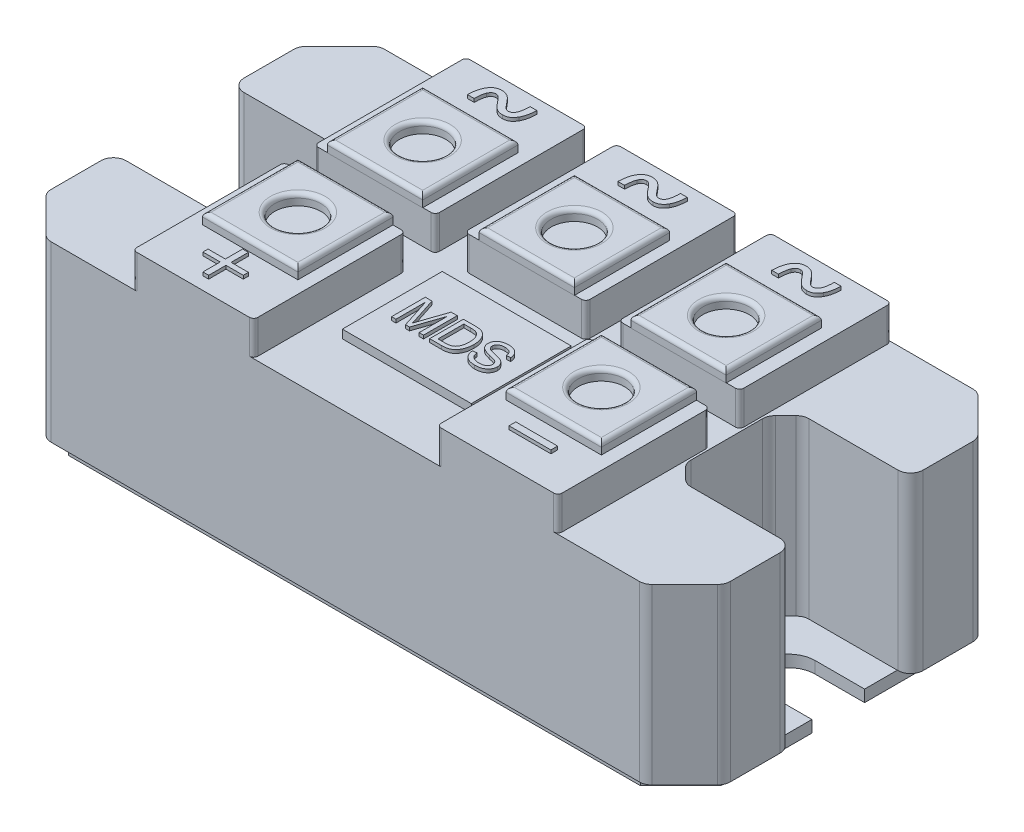
SolidWorks part; units mm, degrees
ref_plane "Front Plane" through (0, 0, 0) normal (0, 0, 1) x (1, 0, 0)
ref_plane "Top Plane" through (0, 0, 0) normal (0, 1, 0) x (1, 0, 0)
ref_plane "Right Plane" through (0, 0, 0) normal (1, 0, 0) x (0, 0, -1)
sketch "Sketch1" plane through (0, 0, 0) normal (0, 1, 0) x (1, 0, 0)
  line L0 (35.9414, 19.3357) -> (39.8357, 15.4414)
  line L1 (-34.8807, 19.775) -> (34.8807, 19.775)
  line L2 (-40.275, 14.3807) -> (-40.275, -14.3807) construction
  line L3 (-34.8807, -19.775) -> (34.8807, -19.775)
  line L4 (40.275, 14.3807) -> (40.275, 8.5)
  line L5 (-37.0738, 18.2032) -> (37.0738, -18.2032) construction
  line L6 (-37.0738, -18.2032) -> (37.0738, 18.2032) construction
  line L7 (38.775, 7) -> (28.2176, 7)
  line L8 (-86.2102, 0) -> (86.2102, 0) construction
  line L9 (0, -37.6305) -> (0, 37.6305) construction
  line L10 (25.475, 4.2574) -> (25.475, -4.2574)
  line L11 (38.775, -7) -> (28.2176, -7)
  line L12 (-35.9414, -19.3357) -> (-39.8357, -15.4414)
  line L13 (-40.275, -8.5) -> (-40.275, -14.3807)
  line L14 (-38.775, -7) -> (-28.2176, -7)
  line L15 (27.157, 6.5607) -> (25.9143, 5.318)
  line L16 (27.5963, 7) -> (25.475, 7) construction
  line L17 (25.475, 7) -> (25.475, 4.8787) construction
  line L18 (27.157, -6.5607) -> (25.9143, -5.318)
  line L19 (27.5963, -7) -> (25.475, -7) construction
  line L20 (25.475, -4.8787) -> (25.475, -7) construction
  line L21 (40.275, 7) -> (40.275, 0) construction
  line L22 (40.275, -8.5) -> (40.275, -14.3807)
  line L23 (40.275, 0) -> (40.275, -7) construction
  line L24 (35.9414, -19.3357) -> (39.8357, -15.4414)
  line L25 (40.275, -15.002) -> (40.275, -19.775) construction
  line L26 (37.0738, -18.2032) -> (40.275, -19.775) construction
  line L27 (35.502, -19.775) -> (40.275, -19.775) construction
  line L28 (40.275, 19.775) -> (40.275, 15.002) construction
  line L29 (37.0738, 18.2032) -> (40.275, 19.775) construction
  line L30 (35.502, 19.775) -> (40.275, 19.775) construction
  line L31 (-27.157, -6.5607) -> (-25.9143, -5.318)
  line L32 (-25.475, 4.2574) -> (-25.475, -4.2574)
  line L33 (-27.157, 6.5607) -> (-25.9143, 5.318)
  line L34 (-38.775, 7) -> (-28.2176, 7)
  line L35 (-40.275, 14.3807) -> (-40.275, 8.5)
  line L36 (-35.9414, 19.3357) -> (-39.8357, 15.4414)
  line L37 (-40.275, 19.775) -> (-34.8807, 19.775) construction
  line L38 (-40.275, 19.775) -> (-37.0738, 18.2032) construction
  line L39 (-40.275, 19.775) -> (-40.275, 14.3807) construction
  line L40 (-40.275, -19.775) -> (-34.8807, -19.775) construction
  line L41 (-40.275, -19.775) -> (-37.0738, -18.2032) construction
  line L42 (-40.275, -14.3807) -> (-40.275, -19.775) construction
  arc A0 (40.275, -8.5) -> (38.775, -7) centre (38.775, -8.5) ccw
  arc A1 (40.275, 8.5) -> (38.775, 7) centre (38.775, 8.5) cw
  arc A2 (40.275, -14.3807) -> (39.8357, -15.4414) centre (38.775, -14.3807) cw
  arc A3 (35.9414, -19.3357) -> (34.8807, -19.775) centre (34.8807, -18.275) cw
  arc A4 (34.8807, 19.775) -> (35.9414, 19.3357) centre (34.8807, 18.275) cw
  arc A5 (40.275, 14.3807) -> (39.8357, 15.4414) centre (38.775, 14.3807) ccw
  arc A6 (27.157, -6.5607) -> (28.2176, -7) centre (28.2176, -5.5) ccw
  arc A7 (25.475, -4.2574) -> (25.9143, -5.318) centre (26.975, -4.2574) ccw
  arc A8 (25.475, 4.2574) -> (25.9143, 5.318) centre (26.975, 4.2574) cw
  arc A9 (27.157, 6.5607) -> (28.2176, 7) centre (28.2176, 5.5) cw
  arc A10 (-35.9414, -19.3357) -> (-34.8807, -19.775) centre (-34.8807, -18.275) ccw
  arc A11 (-40.275, -14.3807) -> (-39.8357, -15.4414) centre (-38.775, -14.3807) ccw
  arc A12 (-40.275, -8.5) -> (-38.775, -7) centre (-38.775, -8.5) cw
  arc A13 (-27.157, -6.5607) -> (-28.2176, -7) centre (-28.2176, -5.5) cw
  arc A14 (-25.475, -4.2574) -> (-25.9143, -5.318) centre (-26.975, -4.2574) cw
  arc A15 (-25.475, 4.2574) -> (-25.9143, 5.318) centre (-26.975, 4.2574) ccw
  arc A16 (-27.157, 6.5607) -> (-28.2176, 7) centre (-28.2176, 5.5) ccw
  arc A17 (-40.275, 8.5) -> (-38.775, 7) centre (-38.775, 8.5) ccw
  arc A18 (-40.275, 14.3807) -> (-39.8357, 15.4414) centre (-38.775, 14.3807) cw
  arc A19 (-34.8807, 19.775) -> (-35.9414, 19.3357) centre (-34.8807, 18.275) ccw
  point P0 (0, 0)
  point P13 (0, 0)
  point P16 (0, 0)
  point P18 (25.475, 0)
  point P62 (86.2102, 0)
  dimension "D9" = 1.5
  dimension "D10" = 1.5
  dimension "D12" = 1.5
  dimension "D1" = 39.55
  dimension "D2" = 80.55
  dimension "D3" = 6.75
  dimension "D4" = 135
  dimension "D5" = 14
  dimension "D6" = 14.8
  dimension "D7" = 3
  dimension "D8" = 135
extrude "Boss-Extrude1" add sketch "Sketch1" along normal blind 20.6
sketch "Sketch2" plane through (0, 0, 0) normal (0, -1, 0) x (1, 0, 0)
  line L0 (33.927, 18.7) -> (38.7, 13.927)
  line L1 (-33.927, -18.7) -> (33.927, -18.7)
  line L2 (-38.7, -13.927) -> (-38.7, 13.927)
  line L3 (-33.927, 18.7) -> (33.927, 18.7)
  line L4 (38.7, -13.927) -> (38.7, -3.125)
  line L5 (-35.482, -17.145) -> (35.482, 17.145) construction
  line L6 (-35.482, 17.145) -> (35.482, -17.145) construction
  line L7 (33.927, 18.7) -> (38.7, 18.7) construction
  line L8 (35.482, 17.145) -> (38.7, 18.7) construction
  line L9 (38.7, 13.927) -> (38.7, 18.7) construction
  line L10 (0, 0) -> (29.7, 0) construction
  line L11 (0, 0) -> (0, 37.1969) construction
  line L12 (38.7, 3.125) -> (32.825, 3.125)
  line L13 (29.7, 0) -> (29.7, 5.404) construction
  line L14 (32.825, -3.125) -> (38.7, -3.125)
  line L15 (38.7, 0) -> (38.7, 3.125) construction
  line L16 (38.7, 3.125) -> (38.7, 13.927)
  line L17 (29.7, 0) -> (38.7, 0) construction
  line L18 (38.7, 0) -> (45.83, 0) construction
  line L19 (38.7, -3.125) -> (38.7, 0) construction
  line L20 (-36.45, 0) -> (-38.7, 0) construction
  line L21 (33.927, -18.7) -> (38.7, -13.927)
  line L22 (38.7, -18.7) -> (38.7, -13.927) construction
  line L23 (35.482, -17.145) -> (38.7, -18.7) construction
  line L24 (33.927, -18.7) -> (38.7, -18.7) construction
  line L25 (-33.927, 18.7) -> (-38.7, 13.927)
  line L26 (-33.927, -18.7) -> (-38.7, -13.927)
  line L27 (-38.7, 18.7) -> (-33.927, 18.7) construction
  line L28 (-38.7, 18.7) -> (-35.482, 17.145) construction
  line L29 (-38.7, 13.927) -> (-38.7, 18.7) construction
  line L30 (-38.7, -18.7) -> (-38.7, -13.927) construction
  line L31 (-38.7, -18.7) -> (-35.482, -17.145) construction
  line L32 (-38.7, -18.7) -> (-33.927, -18.7) construction
  arc A0 (32.825, 3.125) -> (32.825, -3.125) centre (32.825, 0) ccw
  circle A1 centre (-33.325, 0) radius 3.125
  point P0 (0, 0)
  dimension "D8" = 6.25
  dimension "D1" = 37.4
  dimension "D2" = 77.4
  dimension "D3" = 6.75
  dimension "D4" = 45
  dimension "D5" = 6.25
  dimension "D6" = 9
  dimension "D7" = 2.25
extrude "Boss-Extrude2" add sketch "Sketch2" along normal blind 1.4
sketch "Sketch3" plane through (0, 20.6, 0) normal (0, 1, 0) x (1, 0, 0)
  line L0 (0, 25.2109) -> (0, -27.9325) construction
  line L1 (-42.4001, 0) -> (48.0582, 0) construction
  line L2 (34.8807, 19.775) -> (-34.8807, 19.775) construction
  line L3 (-25.225, 19.775) -> (-10.875, 19.775)
  line L4 (-25.225, 19.775) -> (-25.225, 1.775)
  line L5 (-25.225, 1.775) -> (-10.875, 1.775)
  line L6 (-10.875, 19.775) -> (-10.875, 1.775)
  line L7 (-7.375, 19.775) -> (6.975, 19.775)
  line L8 (-7.375, 19.775) -> (-7.375, 1.775)
  line L9 (-7.375, 1.775) -> (6.975, 1.775)
  line L10 (6.975, 19.775) -> (6.975, 1.775)
  line L11 (-25.225, -1.775) -> (-10.875, -1.775)
  line L12 (-10.875, -19.775) -> (-10.875, -1.775)
  line L13 (-25.225, -19.775) -> (-10.875, -19.775)
  line L14 (-25.225, -19.775) -> (-25.225, -1.775)
  line L15 (25.225, -19.775) -> (25.225, -1.775)
  line L16 (25.225, -19.775) -> (10.875, -19.775)
  line L17 (10.875, -19.775) -> (10.875, -1.775)
  line L18 (25.225, -1.775) -> (10.875, -1.775)
  line L19 (25.225, 1.775) -> (10.875, 1.775)
  line L20 (10.875, 19.775) -> (10.875, 1.775)
  line L21 (25.225, 19.775) -> (10.875, 19.775)
  line L22 (25.225, 19.775) -> (25.225, 1.775)
  dimension "D1" = 14.35
  dimension "D2" = 18
  dimension "D3" = 3.5
  dimension "D4" = 50.45
extrude "Boss-Extrude3" add sketch "Sketch3" along normal blind 4
sketch "Sketch4" plane through (0, 20.6, 0) normal (0, 1, 0) x (1, 0, 0)
  line L0 (0, 0) -> (0, -16.2581) construction
  line L1 (-7.65, -0.625) -> (7.65, -0.625)
  line L2 (-7.65, -0.625) -> (-7.65, -12.475)
  line L3 (-7.65, -12.475) -> (7.65, -12.475)
  line L4 (7.65, -0.625) -> (7.65, -12.475)
  line L5 (-7.65, -0.625) -> (7.65, -12.475) construction
  line L6 (-7.65, -12.475) -> (7.65, -0.625) construction
  line L7 (-10.875, -19.775) -> (10.875, -19.775) construction
  point P0 (0, -6.55)
  point P8 (0, 0)
  dimension "D1" = 7.3
  dimension "D2" = 15.3
  dimension "D3" = 11.85
extrude "Boss-Extrude4" add sketch "Sketch4" along normal blind 1
fillet "Fillet1" radius 0.5 20 edges at (-25.225, 22.6, 1.775) (-25.225, 22.6, -19.775) (-7.375, 22.6, -19.775) (10.875, 22.6, -19.775) (10.875, 22.6, 1.775) (-10.875, 22.6, -19.775) (25.225, 22.6, -19.775) (6.975, 22.6, -19.775) (25.225, 22.6, 1.775) (10.875, 22.6, 19.775) (10.875, 22.6, -1.775) (25.225, 22.6, -1.775) (25.225, 22.6, 19.775) (-25.225, 22.6, 19.775) (-25.225, 22.6, -1.775) (6.975, 22.6, -1.775) (-7.375, 22.6, -1.775) (-10.875, 22.6, -1.775) (-10.875, 22.6, 1.775) (-10.875, 22.6, 19.775)
sketch "Sketch5" plane through (0, 24.6, 0) normal (0, 1, 0) x (1, 0, 0)
  line L0 (0, 24.9244) -> (0, -26.2852) construction
  line L1 (-23.65, 13.05) -> (-12.35, 13.05)
  line L2 (-23.65, 13.05) -> (-23.65, 1.75)
  line L3 (-23.65, 1.75) -> (-12.35, 1.75)
  line L4 (-12.35, 13.05) -> (-12.35, 1.75)
  line L5 (-23.65, 13.05) -> (-12.35, 1.75) construction
  line L6 (-23.65, 1.75) -> (-12.35, 13.05) construction
  line L7 (34.9514, 0) -> (-42.9731, 0) construction
  line L8 (-23.65, -1.75) -> (-12.35, -1.75)
  line L9 (-12.35, -13.05) -> (-12.35, -1.75)
  line L10 (-23.65, -13.05) -> (-12.35, -13.05)
  line L11 (-23.65, -13.05) -> (-23.65, -1.75)
  line L12 (-5.65, 13.05) -> (-5.65, 1.75)
  line L13 (-5.65, 13.05) -> (5.65, 13.05)
  line L14 (5.65, 13.05) -> (5.65, 1.75)
  line L15 (-5.65, 1.75) -> (5.65, 1.75)
  line L16 (23.65, -13.05) -> (23.65, -1.75)
  line L17 (23.65, -13.05) -> (12.35, -13.05)
  line L18 (12.35, -13.05) -> (12.35, -1.75)
  line L19 (23.65, -1.75) -> (12.35, -1.75)
  line L20 (23.65, 1.75) -> (12.35, 1.75)
  line L21 (12.35, 13.05) -> (12.35, 1.75)
  line L22 (23.65, 13.05) -> (12.35, 13.05)
  line L23 (23.65, 13.05) -> (23.65, 1.75)
  circle A0 centre (-18, 7.4) radius 2.75
  circle A1 centre (-18, -7.4) radius 2.75
  circle A2 centre (0, 7.4) radius 2.75
  circle A3 centre (18, -7.4) radius 2.75
  circle A4 centre (18, 7.4) radius 2.75
  point P0 (-18, 7.4)
  dimension "D4" = 5.5
  dimension "D1" = 11.3
  dimension "D2" = 3.5
  dimension "D3" = 18
  dimension "D6" = 6.7
  dimension "D5" = 2
extrude "Boss-Extrude5" add sketch "Sketch5" along normal blind 1.3
fillet "Fillet2" radius 0.5 25 edges at (-18, 25.9, 4.65) (-18, 25.9, 1.75) (-12.35, 25.9, 7.4) (-18, 25.9, 13.05) (-23.65, 25.9, 7.4) (18, 25.9, -10.15) (18, 25.9, -1.75) (12.35, 25.9, -7.4) (18, 25.9, -13.05) (23.65, 25.9, -7.4) (18, 25.9, 10.15) (12.35, 25.9, 7.4) (18, 25.9, 1.75) (23.65, 25.9, 7.4) (18, 25.9, 13.05) (0, 25.9, -4.65) (-5.65, 25.9, -7.4) (0, 25.9, -13.05) (5.65, 25.9, -7.4) (0, 25.9, -1.75) (-18, 25.9, -4.65) (-18, 25.9, -1.75) (-23.65, 25.9, -7.4) (-18, 25.9, -13.05) (-12.35, 25.9, -7.4)
sketch "Sketch6" plane through (0, 21.6, 0) normal (0, 1, 0) x (1, 0, 0)
  line L0 (-7.65, -8.675) -> (7.65, -8.675) construction
  line L1 (-7.65, -0.625) -> (-7.65, -12.475) construction
  line L2 (7.65, -12.475) -> (7.65, -0.625) construction
  line L3 (-7.65, -12.475) -> (7.65, -12.475) construction
  text T0 "MDS" font "Arial Narrow" height 4
  point P4 (7.65, -8.8811)
  dimension "D1" = 3.8
extrude "Boss-Extrude6" add sketch "Sketch6" along normal blind 0.4
sketch "Sketch7" plane through (0, 24.6, 0) normal (0, 1, 0) x (1, 0, 0)
  line L0 (-25.225, 13.775) -> (-10.875, 13.775) construction
  line L1 (-25.225, 19.275) -> (-25.225, 2.275) construction
  line L2 (-10.875, 2.275) -> (-10.875, 19.275) construction
  line L3 (-7.375, 13.775) -> (6.975, 13.775) construction
  line L4 (-7.375, 19.275) -> (-7.375, 2.275) construction
  line L5 (6.975, 2.275) -> (6.975, 19.275) construction
  line L6 (10.875, 13.775) -> (25.225, 13.775) construction
  line L7 (10.875, 19.275) -> (10.875, 2.275) construction
  line L8 (25.225, 2.275) -> (25.225, 19.275) construction
  line L9 (-11.375, 19.775) -> (-24.725, 19.775) construction
  line L10 (-25.225, -18.575) -> (-10.875, -18.575) construction
  line L11 (-25.225, -2.275) -> (-25.225, -19.275) construction
  line L12 (-10.875, -19.275) -> (-10.875, -2.275) construction
  line L13 (10.875, -18.575) -> (25.225, -18.575) construction
  line L14 (10.875, -2.275) -> (10.875, -19.275) construction
  line L15 (25.225, -19.275) -> (25.225, -2.275) construction
  line L16 (-24.725, -19.775) -> (-11.375, -19.775) construction
  text T0 "~" font "Tahoma" height 7
  text T1 "~" font "Tahoma" height 7
  text T2 "~" font "Tahoma" height 7
  text T3 "+" font "Tahoma" height 6
  text T4 "-" font "Tahoma" height 7
  dimension "D1" = 6
  dimension "D2" = 1.2
extrude "Boss-Extrude7" add sketch "Sketch7" along normal blind 0.4
